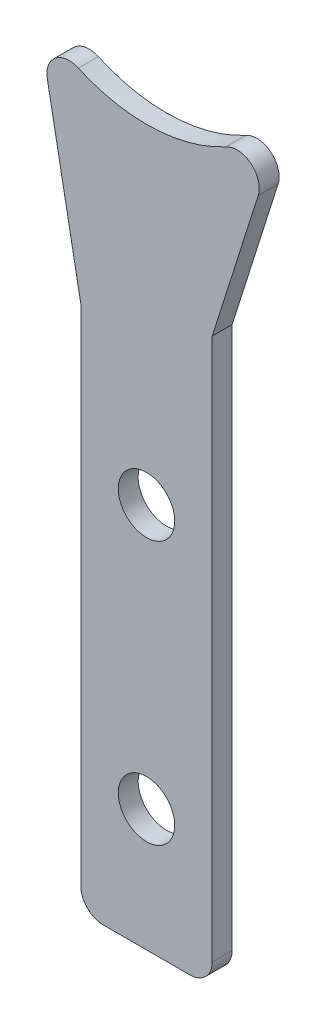
SolidWorks part; units mm, degrees
material "ASTM A36 Steel"
ref_plane "X-Y Datum" through (0, 0, 0) normal (0, 0, 1) x (1, 0, 0)
ref_plane "X-Z Datum" through (0, 0, 0) normal (0, 1, 0) x (1, 0, 0)
ref_plane "Y-Z Datum" through (0, 0, 0) normal (1, 0, 0) x (0, 0, -1)
sketch "Sketch1" plane through (0, 0, 0) normal (0, 0, 1) x (1, 0, 0)
  line L0 (2.16, -15.8959) -> (2.16, -25.6179)
  line L2 (-3.0789, -25.6179) -> (-3.0789, 16.3821)
  line L5 (-3.0789, -25.6179) -> (7.3993, -25.6179)
  line L6 (-3.0789, 16.3821) -> (2.16, 16.3821)
  line L7 (7.3993, -25.6179) -> (7.3993, 4.3814)
  line L8 (-3.0789, 16.3821) -> (-6.508, 34.6228)
  line L9 (7.3993, 4.3814) -> (7.3993, 19.3814)
  line L10 (2.16, -15.8959) -> (2.16, -25.6179)
  line L11 (7.3993, 19.3814) -> (13.0185, 37.0706)
  circle A5 centre (2.159, 44.5921) radius 13.21
  circle A6 centre (2.16, -0.8962) radius 2 construction
  circle A7 centre (2.16, -15.8959) radius 2 construction
  point P0 (0, 0)
  point P11 (0, 0)
  point P15 (0, 0)
  point P19 (0, 0)
  point P20 (0, 0)
  dimension "D1" = 26.42
  dimension "D2" = 4
  dimension "D3" = 4
  dimension "D6" = 28.21
  dimension "D4" = 14.9997
  dimension "D5" = 9.722
  dimension "D7" = 42
  dimension "D8" = 10.4782
extrude "Boss-Extrude1" add sketch "Sketch1" along normal blind 1.5875
fillet "Fillet2" radius 1.778 4 edges at (7.3993, -25.6179, 0.7937) (-3.0789, -25.6179, 0.7937) (-6.508, 34.6228, 0.7937) (13.0185, 37.0706, 0.7937)
sketch "Sketch4" plane through (0, 0, 1.5875) normal (0, 0, 1) x (1, 0, 0)
  point P7 (2.1602, 5.1038)
  point P10 (2.1602, -15.8959)
hole_wizard "M4 Clearance Hole2" positions "Sketch4" profile "Sketch5" hole size "M4" standard "ANSI Metric" end condition through all
sketch "Sketch5" plane through (2.1602, 5.1038, 1.5875) normal (1, 0, 0) x (0, -1, 0)
  line L0 (0, 0) -> (0, 1.5875)
  line L1 (0, 1.5875) -> (2.25, 1.5875)
  line L2 (2.25, 1.5875) -> (2.25, 0)
  line L5 (2.25, 0) -> (0, 0)
  line L11 (0, -6.35) -> (0, 107.95) construction
  dimension "Thru Hole Dia." = 4.5
  dimension "Thru Hole Depth" = 1.5875
